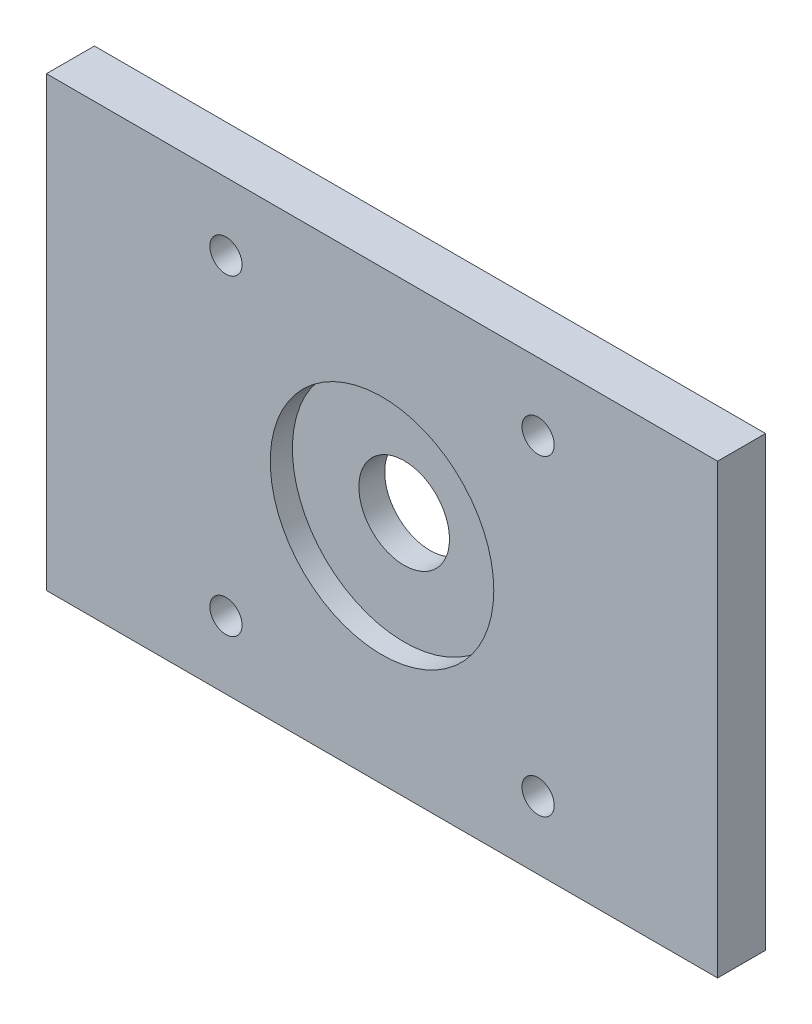
SolidWorks part; units mm, degrees
ref_plane "Front Plane" through (0, 0, 0) normal (0, 0, 1) x (1, 0, 0)
ref_plane "Top Plane" through (0, 0, 0) normal (0, 1, 0) x (1, 0, 0)
ref_plane "Right Plane" through (0, 0, 0) normal (1, 0, 0) x (0, 0, -1)
sketch "Sketch1" plane through (0, 0, 0) normal (0, 0, 1) x (1, 0, 0)
  line L1 (0, 0) -> (66.6496, 0)
  line L2 (0, 0) -> (0, 44.45)
  line L3 (0, 44.45) -> (66.6496, 44.45)
  line L4 (66.6496, 0) -> (66.6496, 44.45)
  dimension "D1" = 66.6496
  dimension "D2" = 44.45
extrude "Boss-Extrude1" add sketch "Sketch1" along normal blind 4.7625
hole_wizard "M3 Clearance Hole1" positions "Sketch3" profile "Sketch5" hole size "M3" standard "ANSI Metric" end condition through all
sketch "Sketch3" plane through (0, 0, 4.7625) normal (0, 0, 1) x (1, 0, 0)
  line L0 (0, 44.45) -> (66.6496, 0) construction
  line L2 (17.8248, 6.725) -> (48.8248, 6.725) construction
  line L3 (17.8248, 6.725) -> (17.8248, 37.725) construction
  line L4 (17.8248, 37.725) -> (48.8248, 37.725) construction
  line L5 (48.8248, 6.725) -> (48.8248, 37.725) construction
  line L6 (17.8248, 6.725) -> (48.8248, 37.725) construction
  line L7 (17.8248, 37.725) -> (48.8248, 6.725) construction
  point P7 (48.8248, 37.725)
  point P156 (17.8248, 6.725)
  point P157 (17.8248, 37.725)
  point P158 (48.8248, 6.725)
  dimension "D1" = 31
  dimension "D2" = 31
sketch "Sketch5" plane through (48.8248, 6.725, 4.7625) normal (1, 0, 0) x (0, -1, 0)
  line L0 (0, 0) -> (0, 4.7625)
  line L1 (0, 4.7625) -> (1.6, 4.7625)
  line L2 (1.6, 4.7625) -> (1.6, 0)
  line L5 (1.6, 0) -> (0, 0)
  line L11 (0, -6.35) -> (0, 107.95) construction
  dimension "Thru Hole Dia." = 3.2
  dimension "Thru Hole Depth" = 4.7625
sketch "Sketch6" plane through (0, 0, 4.7625) normal (0, 0, 1) x (1, 0, 0)
  line L0 (0, 44.45) -> (66.6496, 0) construction
  circle A0 centre (33.3248, 22.225) radius 11.1
  dimension "D1" = 22.2
extrude "Cut-Extrude1" cut sketch "Sketch6" against normal blind 2.2
sketch "Sketch7" plane through (0, 0, 2.5625) normal (0, 0, 1) x (1, 0, 0)
  circle A0 centre (33.3248, 22.225) radius 4.5
  dimension "D1" = 9
extrude "Cut-Extrude2" cut sketch "Sketch7" against normal through all
